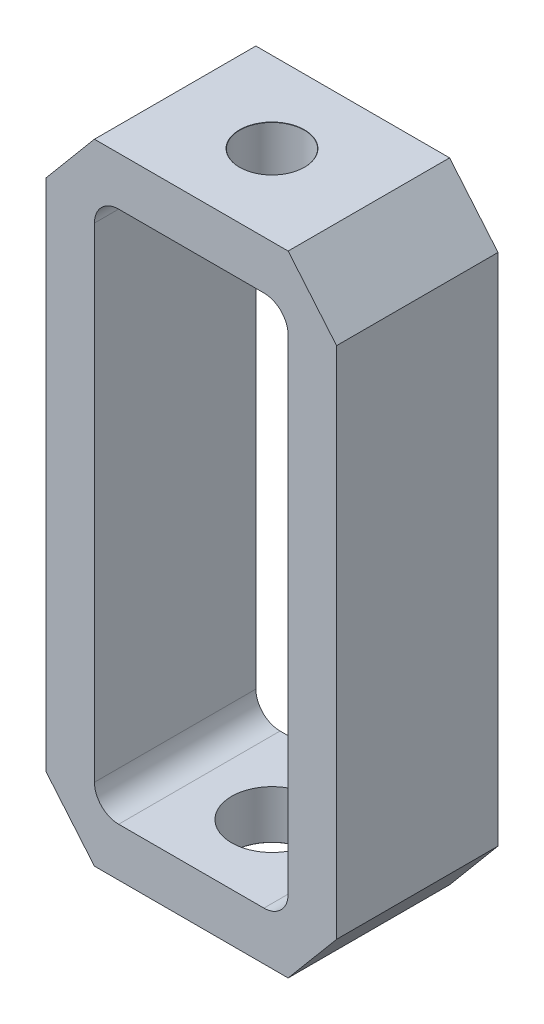
SolidWorks part; units mm, degrees
material "AISI 1045 Steel, cold drawn"
ref_plane "Front Plane" through (0, 0, 0) normal (0, 0, 1) x (1, 0, 0)
ref_plane "Top Plane" through (0, 0, 0) normal (0, 1, 0) x (1, 0, 0)
ref_plane "Right Plane" through (0, 0, 0) normal (1, 0, 0) x (0, 0, -1)
sketch "Sketch1" plane through (0, 0, 0) normal (0, 0, 1) x (1, 0, 0)
  line L0 (-12, -33) -> (-12, 33)
  line L5 (12, -33) -> (12, 33)
  line L6 (-12, 33) -> (12, 33)
  line L7 (0, 13.3234) -> (0, -8.3658) construction
  line L8 (-10.1474, 0) -> (11.2319, 0) construction
  line L9 (-18, -31.8495) -> (-18, 31.8495)
  line L10 (-18, 31.8495) -> (-12, 39)
  line L11 (-12, 39) -> (12, 39)
  line L12 (18, -31.8495) -> (18, 31.8495)
  line L13 (18, 31.8495) -> (12, 39)
  line L14 (18, -31.8495) -> (12, -39)
  line L15 (-12, -39) -> (12, -39)
  line L16 (-18, -31.8495) -> (-12, -39)
  line L17 (-12, -33) -> (12, -33)
  point P17 (0, 33)
  point P21 (0, 39)
  point P22 (18, 0)
  point P25 (-18, 0)
  point P26 (-12, 0)
  point P27 (12, 0)
  dimension "D1" = 39
  dimension "D2" = 6
  dimension "D3" = 6
  dimension "D4" = 24
  dimension "D6" = 220
extrude "Boss-Extrude1" add sketch "Sketch1" along normal mid plane 20 contours L9 L16 L15 L14 L12 L13 L11 L10 L17 L0 L6 L5
hole_wizard "Ø8.0mm Dowel Hole1" positions "3DSketch4" profile "Sketch6" hole size "Ø8.0" standard "ISO"
sketch3d "3DSketch4"
  line L1 (-12, 39, -10) -> (12, 39, -10) construction
  line L2 (-12, 39, 10) -> (-12, 39, -10) construction
  point P0 (0, 39, 0)
  point P9 (0, 39, -10)
  point P12 (-12, 39, 0)
sketch "Sketch6" plane through (0, 39, 0) normal (1, 0, 0) x (0, 0, 1)
  line L0 (0, 0) -> (0, 26.9034)
  line L1 (0, 26.9034) -> (4, 24.5)
  line L2 (4, 24.5) -> (4, 0.025)
  line L3 (4, 0.025) -> (4.025, 0)
  line L5 (4.025, 0) -> (0, 0)
  line L6 (-4, 0.025) -> (-4.025, 0) construction
  line L10 (0, 26.9034) -> (-4, 24.5) construction
  line L11 (0, -6.35) -> (0, 107.95) construction
  dimension "Hole Dia." = 8
  dimension "Hole Depth" = 24.5
  dimension "Near C'Sink Dia." = 8.05
  dimension "Near C'Sink Angle" = 90
  dimension "Drill Angle" = 118
hole_wizard "Ø10.0mm Dowel Hole2" positions "3DSketch5" profile "Sketch7" hole size "Ø10.0" standard "ISO"
sketch3d "3DSketch5"
  line L0 (-12, -39, 10) -> (-12, -39, -10) construction
  line L1 (-12, -39, -10) -> (12, -39, -10) construction
  point P0 (0, -39, 0)
  point P5 (-12, -39, 0)
  point P8 (0, -39, -10)
sketch "Sketch7" plane through (0, -39, 0) normal (1, 0, 0) x (0, 0, -1)
  line L0 (0, 0) -> (0, 27.5043)
  line L1 (0, 27.5043) -> (5, 24.5)
  line L2 (5, 24.5) -> (5, 0.025)
  line L3 (5, 0.025) -> (5.025, 0)
  line L5 (5.025, 0) -> (0, 0)
  line L6 (-5, 0.025) -> (-5.025, 0) construction
  line L10 (0, 27.5043) -> (-5, 24.5) construction
  line L11 (0, -6.35) -> (0, 107.95) construction
  dimension "Hole Dia." = 10
  dimension "Hole Depth" = 24.5
  dimension "Near C'Sink Dia." = 10.05
  dimension "Near C'Sink Angle" = 90
  dimension "Drill Angle" = 118
fillet "Fillet1" radius 3 4 edges at (12, -33, 0) (-12, -33, 0) (12, 33, 0) (-12, 33, 0)
